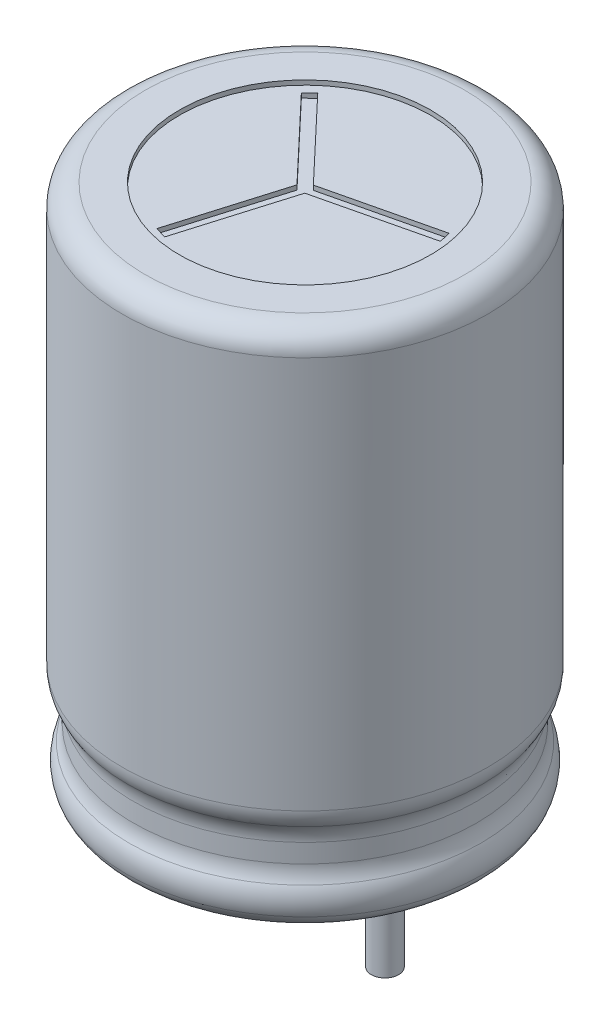
SolidWorks part; units mm, degrees
ref_plane "Front Plane" through (0, 0, 0) normal (0, 0, 1) x (1, 0, 0)
ref_plane "Top Plane" through (0, 0, 0) normal (0, 1, 0) x (1, 0, 0)
ref_plane "Right Plane" through (0, 0, 0) normal (1, 0, 0) x (0, 0, -1)
sketch "Sketch1" plane through (0, 0, 0) normal (0, 0, 1) x (1, 0, 0)
  line L0 (4, 11.5) -> (0, 11.5)
  line L1 (0, 11.5) -> (0, 0)
  line L2 (0, 0) -> (3.6439, 0)
  line L3 (3.7604, 1.2326) -> (3.7604, 1.6424)
  line L4 (4, 2.4076) -> (4, 11.5)
  line L5 (0, 11.5) -> (0, 0) construction
  arc A0 (3.6439, 0) -> (3.8514, 0.8953) centre (3.2715, 0.558) ccw
  arc A1 (3.8514, 0.8953) -> (3.7604, 1.2326) centre (4.4312, 1.2326) cw
  arc A2 (3.7604, 1.6424) -> (3.8802, 2.025) centre (4.4313, 1.6424) cw
  arc A3 (3.8802, 2.025) -> (4, 2.4076) centre (3.3292, 2.4076) ccw
  dimension "D1" = 11.5
  dimension "D2" = 4
revolve "Revolve1" add sketch "Sketch1" angle 360 about L5
sketch "Sketch2" plane through (0, 11.5, 0) normal (0, 1, 0) x (-1, 0, 0)
  circle A0 centre (0, 0) radius 2.75
extrude "Cut-Extrude1" cut sketch "Sketch2" against normal blind 0.1
sketch "Sketch3" plane through (0, 11.4, 0) normal (0, 1, 0) x (-1, 0, 0)
  line L0 (1.6535, -1.9323) -> (1.838, -1.7577)
  line L1 (1.838, -1.7577) -> (0.1426, 0.034)
  line L2 (0.1426, 0.034) -> (0.8467, 2.3981)
  line L3 (0.8467, 2.3981) -> (0.6032, 2.4706)
  line L4 (0.6032, 2.4706) -> (-0.1008, 0.1065)
  line L5 (-0.1008, 0.1065) -> (-2.5002, -0.4658)
  line L6 (-2.5002, -0.4658) -> (-2.4412, -0.7129)
  line L7 (-2.4412, -0.7129) -> (-0.0419, -0.1405)
  line L8 (-0.0419, -0.1405) -> (1.6535, -1.9323)
extrude "Cut-Extrude2" cut sketch "Sketch3" against normal blind 0.1
ref_plane "Plane1" through (0, 0, 0) normal (0, 0, -1) x (-1, 0, 0)
sketch "Sketch4" plane through (0, 0, 0) normal (0, 0, -1) x (-1, 0, 0)
  line L0 (-2.05, -2.5) -> (-1.75, -2.5)
  line L1 (-1.75, -2.5) -> (-1.75, 0)
  line L2 (-1.75, 0) -> (-2.05, 0)
  line L3 (-2.05, 0) -> (-2.05, -2.5)
  line L4 (-1.75, -2.5) -> (-1.75, 0) construction
revolve "Revolve2" add sketch "Sketch4" angle 360 about L4
sketch "Sketch5" plane through (0, 0, 0) normal (0, 0, -1) x (-1, 0, 0)
  line L0 (1.45, -2.5) -> (1.75, -2.5)
  line L1 (1.75, -2.5) -> (1.75, 0)
  line L2 (1.75, 0) -> (1.45, 0)
  line L3 (1.45, 0) -> (1.45, -2.5)
  line L4 (1.75, -2.5) -> (1.75, 0) construction
revolve "Revolve3" add sketch "Sketch5" angle 360 about L4
fillet "Fillet1" radius 0.5 2 edges at (4, 11.5, 0) (3.6439, 0, 0)
